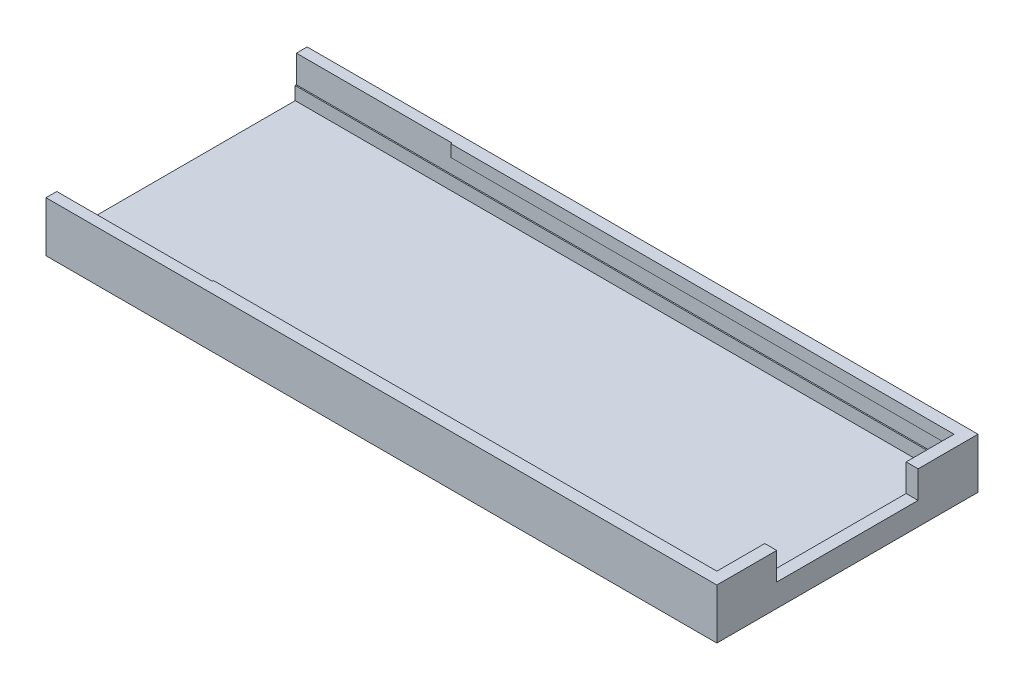
SolidWorks part; units mm, degrees
ref_plane "Front Plane" through (0, 0, 0) normal (0, 0, 1) x (1, 0, 0)
ref_plane "Top Plane" through (0, 0, 0) normal (0, 1, 0) x (1, 0, 0)
ref_plane "Right Plane" through (0, 0, 0) normal (1, 0, 0) x (0, 0, -1)
sketch "Sketch1" plane through (0, 0, 0) normal (1, 0, 0) x (0, 0, -1)
  line L0 (0, 0) -> (0, 4.2)
  line L1 (0, 4.2) -> (1, 4.2)
  line L2 (1, 4.2) -> (1, 3.2)
  line L3 (1, 3.2) -> (0.9, 3.2)
  line L4 (0.9, 3.2) -> (0.9, 1.9137)
  line L5 (0.9, 1.9137) -> (1, 1.9137)
  line L6 (1, 1.9137) -> (1, 0.8137)
  line L7 (1, 0.8137) -> (20.8, 0.8138)
  line L8 (10.9, 0.8137) -> (10.9, 0)
  line L9 (21.8, 0) -> (0, 0)
  line L10 (21.8, 0) -> (21.8, 4.2)
  line L11 (20.8, 1.9138) -> (20.8, 0.8138)
  line L12 (20.9, 1.9138) -> (20.8, 1.9138)
  line L13 (20.9, 3.2) -> (20.9, 1.9138)
  line L14 (20.8, 3.2) -> (20.9, 3.2)
  line L15 (20.8, 4.2) -> (20.8, 3.2)
  line L16 (21.8, 4.2) -> (20.8, 4.2)
  point P3 (0.9, 2.5569)
  dimension "D1" = 4.2
  dimension "D2" = 9.9
  dimension "D3" = 1
  dimension "D4" = 1
  dimension "D5" = 0.1
  dimension "D6" = 0.1
  dimension "D7" = 1.1
  dimension "D8" = 19.8
extrude "Boss-Extrude1" add sketch "Sketch1" along normal blind 42 contours L9 L8 L7 L6 L5 L4 L3 L2 L1 L0 | L10 L16 L15 L14 L13 L12 L11 L7 L8 L9
sketch "Sketch2" plane through (42, 0, 0) normal (1, 0, 0) x (0, 0, -1)
  line L0 (20.9, 1.9138) -> (20.8, 1.9138) construction
  line L1 (0, 0) -> (21.8, 0)
  line L2 (0, 0) -> (0, 4.2)
  line L3 (0, 4.2) -> (5, 4.2)
  line L4 (21.8, 0) -> (21.8, 4.2)
  line L6 (5, 4.2) -> (5, 1.9138)
  line L7 (5, 1.9138) -> (16.8, 1.9138)
  line L8 (16.8, 4.2) -> (16.8, 1.9138)
  line L9 (16.8, 4.2) -> (21.8, 4.2)
  dimension "D1" = 5
extrude "Boss-Extrude2" add sketch "Sketch2" along normal blind 1 contours L3 L6 L7 L8 L9 L4 L1 L2
sketch "Sketch3" plane through (0, 0, 0) normal (-1, 0, 0) x (0, 0, 1)
  line L0 (-21.8, 4.2) -> (-21.8, 0)
  line L1 (-21.8, 0) -> (0, 0)
  line L2 (0, 0) -> (0, 4.2)
  line L3 (0, 4.2) -> (-0.9, 4.2)
  line L4 (0, 4.2) -> (-1, 4.2) construction
  line L5 (-0.9, 4.2) -> (-0.9, 1.9137)
  line L6 (-1, 0.8137) -> (-20.8, 0.8138)
  line L7 (-20.9, 1.9138) -> (-20.9, 4.2)
  line L8 (-21.8, 4.2) -> (-20.8, 4.2) construction
  line L9 (-20.9, 4.2) -> (-21.8, 4.2)
  line L10 (-20.8, 0.8138) -> (-20.8, 1.9138)
  line L11 (-20.8, 1.9138) -> (-20.9, 1.9138)
  line L12 (-1, 0.8137) -> (-1, 1.9137)
  line L13 (-1, 1.9137) -> (-0.9, 1.9137)
extrude "Boss-Extrude3" add sketch "Sketch3" along normal blind 13
